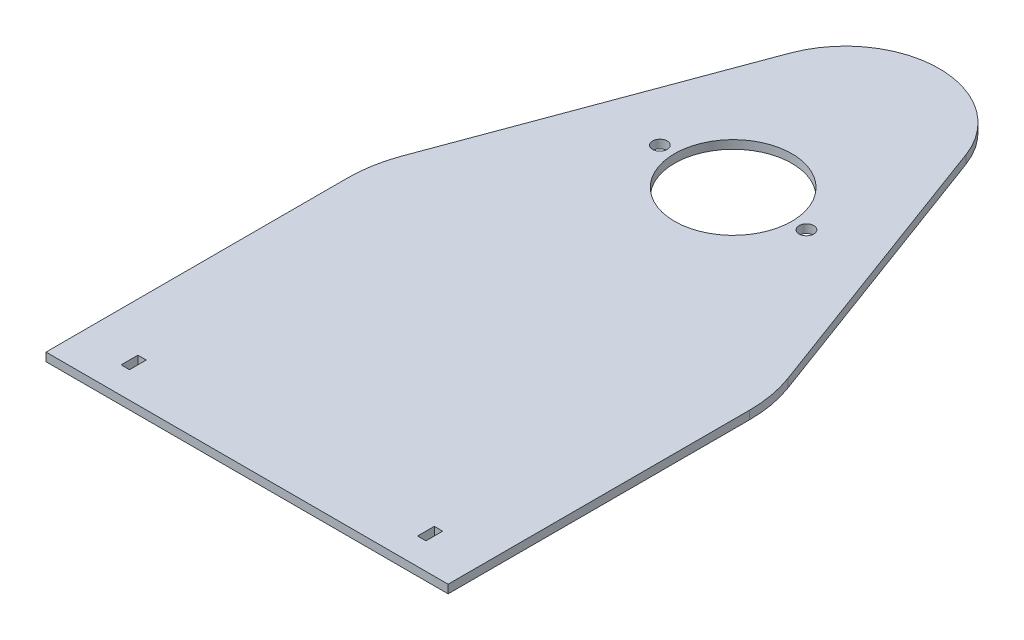
SolidWorks part; units mm, degrees
ref_plane "Front Plane" through (0, 0, 0) normal (0, 0, 1) x (1, 0, 0)
ref_plane "Top Plane" through (0, 0, 0) normal (0, 1, 0) x (1, 0, 0)
ref_plane "Right Plane" through (0, 0, 0) normal (1, 0, 0) x (0, 0, -1)
sketch "Sketch3" plane through (0, 0, 0) normal (0, 1, 0) x (1, 0, 0)
  line L0 (0, 0) -> (0, 114.3)
  line L1 (3.1613, 131.9407) -> (42.8529, 239.1278)
  line L2 (109.5471, 239.1278) -> (149.2387, 131.9407)
  line L3 (152.4, 114.3) -> (152.4, 0)
  line L4 (152.4, 0) -> (0, 0)
  line L5 (76.2, 262.3393) -> (76.2, 0) construction
  line L6 (18.4411, 16.3877) -> (21.6161, 16.3877)
  line L7 (18.4411, 16.3877) -> (18.4411, 10.0377)
  line L8 (18.4411, 10.0377) -> (21.6161, 10.0377)
  line L9 (21.6161, 16.3877) -> (21.6161, 10.0377)
  line L10 (133.9589, 10.0377) -> (130.7839, 10.0377)
  line L11 (130.7839, 16.3877) -> (130.7839, 10.0377)
  line L12 (133.9589, 16.3877) -> (130.7839, 16.3877)
  line L13 (133.9589, 16.3877) -> (133.9589, 10.0377)
  arc A0 (42.8529, 239.1278) -> (109.5471, 239.1278) centre (76.2, 226.7793) cw
  arc A1 (0, 114.3) -> (3.1613, 131.9407) centre (50.8, 114.3) cw
  arc A2 (149.2387, 131.9407) -> (152.4, 114.3) centre (101.6, 114.3) cw
  circle A3 centre (76.2, 184.2441) radius 22.225
  circle A4 centre (103.9813, 184.2441) radius 2.7781
  circle A5 centre (48.4188, 184.2441) radius 2.7781
  dimension "D1" = 35.56
  dimension "D2" = 50.8
  dimension "D3" = 50.8
  dimension "D4" = 114.3
  dimension "D5" = 152.4
  dimension "D6" = 3.175
  dimension "D7" = 6.35
  dimension "D8" = 18.4411
  dimension "D9" = 107.1871
extrude "Boss-Extrude1" add sketch "Sketch3" along normal blind 3.175
